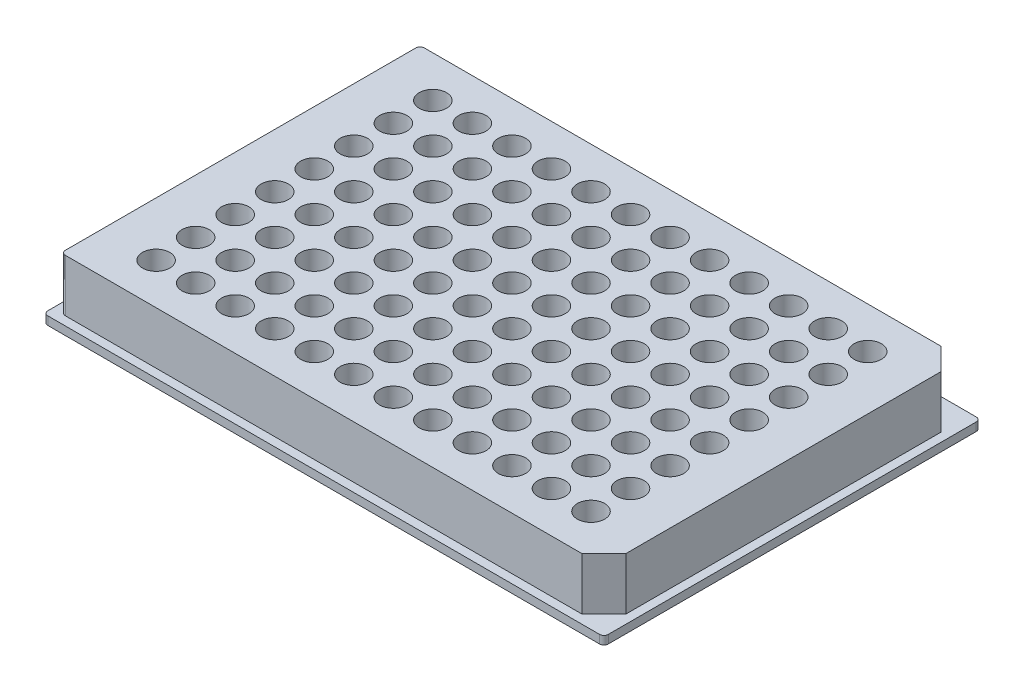
SolidWorks part; units mm, degrees
ref_plane "Front Plane" through (0, 0, 0) normal (0, 0, 1) x (1, 0, 0)
ref_plane "Top Plane" through (0, 0, 0) normal (0, 1, 0) x (1, 0, 0)
ref_plane "Right Plane" through (0, 0, 0) normal (1, 0, 0) x (0, 0, -1)
sketch "Sketch1" plane through (0, 0, 0) normal (0, 1, 0) x (1, 0, 0)
  line L1 (-63.8, 42.875) -> (63.8, 42.875)
  line L2 (-63.8, 42.875) -> (-63.8, -42.875)
  line L3 (-63.8, -42.875) -> (63.8, -42.875)
  line L4 (63.8, 42.875) -> (63.8, -42.875)
  line L5 (-63.8, 42.875) -> (63.8, -42.875) construction
  line L6 (-63.8, -42.875) -> (63.8, 42.875) construction
  point P0 (0, 0)
  dimension "D1" = 127.6
  dimension "D2" = 85.75
extrude "Boss-Extrude1" add sketch "Sketch1" along normal blind 1.9
sketch "Sketch2" plane through (0, 1.9, 0) normal (0, 1, 0) x (1, 0, 0)
  line L0 (-63.8, 42.875) -> (-63.8, -42.875) construction
  line L1 (-61.8, 40.875) -> (61.8, 40.875)
  line L2 (-61.8, 40.875) -> (-61.8, -40.875)
  line L3 (-61.8, -40.875) -> (61.8, -40.875)
  line L4 (61.8, 40.875) -> (61.8, -40.875)
  line L5 (-61.8, 40.875) -> (61.8, -40.875) construction
  line L6 (-61.8, -40.875) -> (61.8, 40.875) construction
  line L7 (63.8, 42.875) -> (-63.8, 42.875) construction
  point P0 (0, 0)
  dimension "D1" = 2
  dimension "D2" = 2
extrude "Boss-Extrude2" add sketch "Sketch2" along normal blind 11.93
chamfer "Chamfer1" distance 5 angle 45 2 edges at (61.8, 7.865, 40.875) (61.8, 7.865, -40.875)
fillet "Fillet1" radius 1 6 edges at (63.8, 0.95, -42.875) (63.8, 0.95, 42.875) (-63.8, 0.95, 42.875) (-63.8, 0.95, -42.875) (-61.8, 7.865, 40.875) (-61.8, 7.865, -40.875)
sketch "Sketch3" plane through (0, 13.83, 0) normal (0, 1, 0) x (1, 0, 0)
  line L2 (-63.8, 41.875) -> (-63.8, -41.875) construction
  line L3 (-62.8, -42.875) -> (62.8, -42.875) construction
  circle A0 centre (-49.5, -31.515) radius 3.105
  point P0 (-49.5, -31.515)
  dimension "D3" = 6.21
  dimension "D1" = 14.3
  dimension "D2" = 11.36
extrude "Cut-Extrude1" cut sketch "Sketch3" against normal blind 11.93
pattern_linear "LPattern1" count 12 spacing 9 along (1, 0, 0) count 8 spacing 9 along (0, 0, -1) of "Cut-Extrude1"
sketch "Sketch4" plane through (0, 0, 0) normal (0, -1, 0) x (1, 0, 0)
  line L24 (62.8, -41.875) -> (62.8, 41.875)
  line L25 (-62.8, -41.875) -> (62.8, -41.875)
  line L26 (-62.8, 41.875) -> (-62.8, -41.875)
  line L27 (62.8, 41.875) -> (-62.8, 41.875)
  line L28 (62.8, -41.875) -> (62.8, 41.875)
  line L29 (-62.8, -41.875) -> (62.8, -41.875)
  line L30 (-62.8, 41.875) -> (-62.8, -41.875)
  line L31 (62.8, 41.875) -> (-62.8, 41.875)
  dimension "D1" = 1
extrude "Cut-Extrude2" cut sketch "Sketch4" against normal blind 1.7
equation "\"D2@Sketch2\"=\"D1@Sketch2\""
